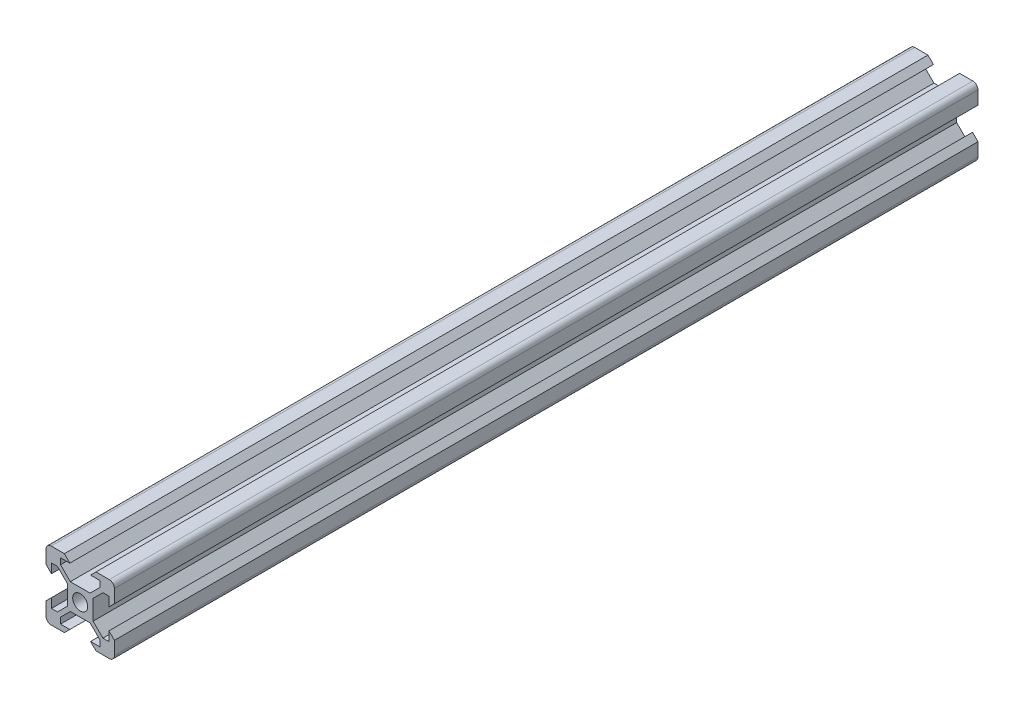
SolidWorks part; units mm, degrees
ref_plane "Front Plane" through (0, 0, 0) normal (0, 0, 1) x (1, 0, 0)
ref_plane "Top Plane" through (0, 0, 0) normal (0, 1, 0) x (1, 0, 0)
ref_plane "Right Plane" through (0, 0, 0) normal (1, 0, 0) x (0, 0, -1)
sketch "Sketch1" plane through (0, 0, 0) normal (0, 0, 1) x (1, 0, 0)
  line L0 (-5.7847, 7.544) -> (-11.512, 13.2713)
  line L1 (-7.544, 7.544) -> (7.544, 7.544)
  line L2 (-7.544, 7.544) -> (-7.544, -7.544)
  line L3 (-7.544, -7.544) -> (7.544, -7.544)
  line L4 (7.544, 7.544) -> (7.544, -7.544)
  line L5 (-7.544, 7.544) -> (7.544, -7.544) construction
  line L6 (-7.544, -7.544) -> (7.544, 7.544) construction
  line L7 (-11.512, 13.2713) -> (-11.512, 16.8)
  line L8 (-11.512, 16.8) -> (-6.052, 16.8)
  line L9 (-6.052, 16.8) -> (-9.252, 20)
  line L10 (-9.252, 20) -> (-17, 20)
  line L11 (-20, 17) -> (-20, 9.252)
  line L12 (-20, 9.252) -> (-16.8, 6.052)
  line L13 (-16.8, 6.052) -> (-16.8, 11.512)
  line L14 (-16.8, 11.512) -> (-13.2713, 11.512)
  line L15 (-13.2713, 11.512) -> (-7.544, 5.7847)
  line L16 (-19.1213, 19.1213) -> (0, 0) construction
  line L17 (13.2713, 11.512) -> (16.8, 11.512)
  line L18 (20, 9.252) -> (20, 17)
  line L19 (17, 20) -> (9.252, 20)
  line L20 (9.252, 20) -> (6.052, 16.8)
  line L21 (6.052, 16.8) -> (11.512, 16.8)
  line L22 (11.512, 16.8) -> (11.512, 13.2713)
  line L23 (11.512, 13.2713) -> (5.7847, 7.544)
  line L24 (7.544, 5.7847) -> (13.2713, 11.512)
  line L25 (16.8, 11.512) -> (16.8, 6.052)
  line L26 (16.8, 6.052) -> (20, 9.252)
  line L27 (19.1213, 19.1213) -> (0, 0) construction
  line L28 (11.512, -13.2713) -> (11.512, -16.8)
  line L29 (9.252, -20) -> (17, -20)
  line L30 (20, -17) -> (20, -9.252)
  line L31 (20, -9.252) -> (16.8, -6.052)
  line L32 (16.8, -6.052) -> (16.8, -11.512)
  line L33 (16.8, -11.512) -> (13.2713, -11.512)
  line L34 (13.2713, -11.512) -> (7.544, -5.7847)
  line L35 (5.7847, -7.544) -> (11.512, -13.2713)
  line L36 (11.512, -16.8) -> (6.052, -16.8)
  line L37 (6.052, -16.8) -> (9.252, -20)
  line L38 (19.1213, -19.1213) -> (0, 0) construction
  line L39 (-13.2713, -11.512) -> (-16.8, -11.512)
  line L40 (-20, -9.252) -> (-20, -17)
  line L41 (-17, -20) -> (-9.252, -20)
  line L42 (-9.252, -20) -> (-6.052, -16.8)
  line L43 (-6.052, -16.8) -> (-11.512, -16.8)
  line L44 (-11.512, -16.8) -> (-11.512, -13.2713)
  line L45 (-11.512, -13.2713) -> (-5.7847, -7.544)
  line L46 (-7.544, -5.7847) -> (-13.2713, -11.512)
  line L47 (-16.8, -11.512) -> (-16.8, -6.052)
  line L48 (-16.8, -6.052) -> (-20, -9.252)
  line L49 (-19.1213, -19.1213) -> (0, 0) construction
  circle A0 centre (0, 0) radius 4.4
  arc A1 (-17, 20) -> (-20, 17) centre (-17, 17) ccw
  arc A2 (20, 17) -> (17, 20) centre (17, 17) ccw
  arc A3 (17, -20) -> (20, -17) centre (17, -17) ccw
  arc A4 (-20, -17) -> (-17, -20) centre (-17, -17) ccw
  point P66 (0, 0)
  dimension "D1" = 8.8
  dimension "D8" = 3
  dimension "D2" = 15.088
  dimension "D3" = 2.488
  dimension "D4" = 8.488
  dimension "D5" = 3.2
  dimension "D6" = 20
  dimension "D7" = 15.2
  dimension "D9" = 4
extrude "Boss-Extrude1" add sketch "Sketch1" along normal mid plane 505 contours L10 A1 L11 L12 L13 L14 L15 L2 L1 L0 L7 L8 L9 | L18 A2 L19 L20 L21 L22 L23 L1 L4 L24 L17 L25 L26 | L40 A4 L41 L42 L43 L44 L45 L3 L2 L46 L39 L47 L48 | L29 A3 L30 L31 L32 L33 L34 L4 L3 L35 L28 L36 L37 | L4 L1 L2 L3 A0
equation "\"longitud\"= 800"
